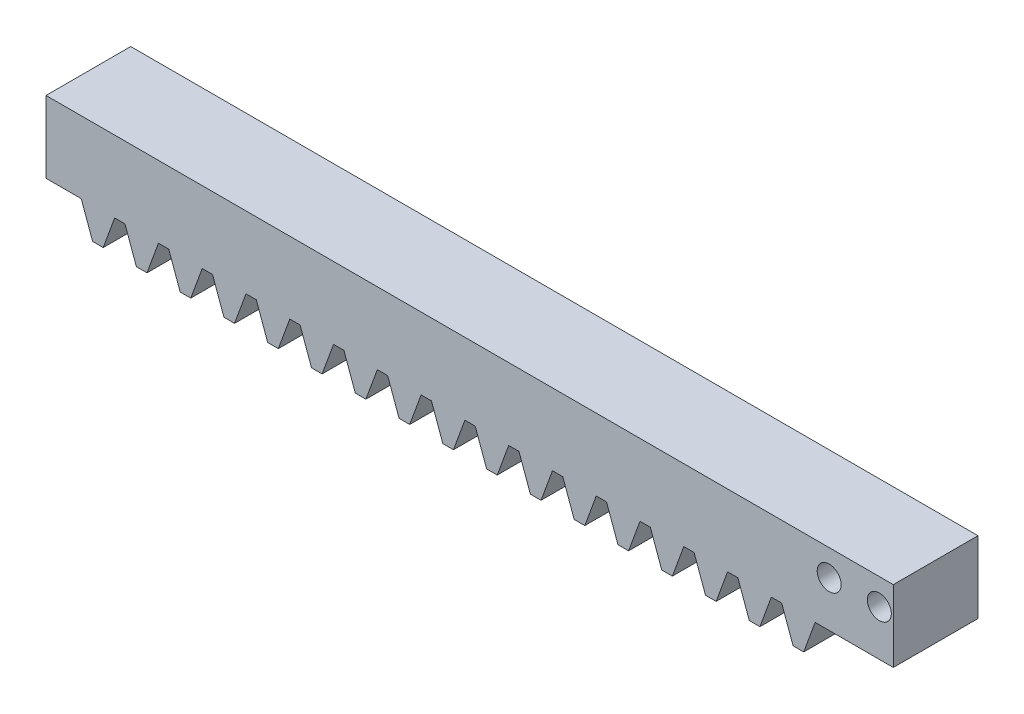
SolidWorks part; units mm, degrees
ref_plane "Front Plane" through (0, 0, 0) normal (0, 0, 1) x (1, 0, 0)
ref_plane "Top Plane" through (0, 0, 0) normal (0, 1, 0) x (1, 0, 0)
ref_plane "Right Plane" through (0, 0, 0) normal (1, 0, 0) x (0, 0, -1)
sketch "Sketch1" plane through (0, 0, 0) normal (0, 0, 1) x (1, 0, 0)
  line L0 (-80, 43.5) -> (-80, 30.625)
  line L1 (-80, 30.625) -> (-73.6867, 30.625)
  line L2 (-73.6867, 30.625) -> (-71.6394, 25)
  line L3 (-71.6394, 25) -> (-69.7323, 25)
  line L4 (-69.7323, 25) -> (-67.6849, 30.625)
  line L5 (-67.6849, 30.625) -> (-65.8328, 30.625)
  line L6 (-65.8328, 30.625) -> (-63.7854, 25)
  line L7 (-63.7854, 25) -> (-61.8783, 25)
  line L8 (-61.8783, 25) -> (-59.831, 30.625)
  line L9 (-59.831, 30.625) -> (-57.9788, 30.625)
  line L10 (-57.9788, 30.625) -> (-55.9314, 25)
  line L11 (-55.9314, 25) -> (-54.0243, 25)
  line L12 (-54.0243, 25) -> (-51.977, 30.625)
  line L13 (-51.977, 30.625) -> (-50.1248, 30.625)
  line L14 (-50.1248, 30.625) -> (-48.0775, 25)
  line L15 (-48.0775, 25) -> (-46.1703, 25)
  line L16 (-46.1703, 25) -> (-44.123, 30.625)
  line L17 (-44.123, 30.625) -> (-42.2708, 30.625)
  line L18 (-42.2708, 30.625) -> (-40.2235, 25)
  line L19 (-40.2235, 25) -> (-38.3163, 25)
  line L20 (-38.3163, 25) -> (-36.269, 30.625)
  line L21 (-36.269, 30.625) -> (-34.4168, 30.625)
  line L22 (-34.4168, 30.625) -> (-32.3695, 25)
  line L23 (-32.3695, 25) -> (-30.4624, 25)
  line L24 (-30.4624, 25) -> (-28.415, 30.625)
  line L25 (-28.415, 30.625) -> (-26.5628, 30.625)
  line L26 (-26.5628, 30.625) -> (-24.5155, 25)
  line L27 (-24.5155, 25) -> (-22.6084, 25)
  line L28 (-22.6084, 25) -> (-20.561, 30.625)
  line L29 (-20.561, 30.625) -> (-18.7089, 30.625)
  line L30 (-18.7089, 30.625) -> (-16.6615, 25)
  line L31 (-16.6615, 25) -> (-14.7544, 25)
  line L32 (-14.7544, 25) -> (-12.7071, 30.625)
  line L33 (-12.7071, 30.625) -> (-10.8549, 30.625)
  line L34 (-10.8549, 30.625) -> (-8.8076, 25)
  line L35 (-8.8076, 25) -> (-6.9004, 25)
  line L36 (-6.9004, 25) -> (-4.8531, 30.625)
  line L37 (-4.8531, 30.625) -> (-3.0009, 30.625)
  line L38 (-3.0009, 30.625) -> (-0.9536, 25)
  line L39 (-0.9536, 25) -> (0.9536, 25)
  line L40 (0.9536, 25) -> (3.0009, 30.625)
  line L41 (3.0009, 30.625) -> (4.8531, 30.625)
  line L42 (4.8531, 30.625) -> (6.9004, 25)
  line L43 (6.9004, 25) -> (8.8076, 25)
  line L44 (8.8076, 25) -> (10.8549, 30.625)
  line L45 (10.8549, 30.625) -> (12.7071, 30.625)
  line L46 (12.7071, 30.625) -> (14.7544, 25)
  line L47 (14.7544, 25) -> (16.6615, 25)
  line L48 (16.6615, 25) -> (18.7089, 30.625)
  line L49 (18.7089, 30.625) -> (20.561, 30.625)
  line L50 (20.561, 30.625) -> (22.6084, 25)
  line L51 (22.6084, 25) -> (24.5155, 25)
  line L52 (24.5155, 25) -> (26.5628, 30.625)
  line L53 (26.5628, 30.625) -> (28.415, 30.625)
  line L54 (28.415, 30.625) -> (30.4624, 25)
  line L55 (30.4624, 25) -> (32.3695, 25)
  line L56 (32.3695, 25) -> (34.4168, 30.625)
  line L57 (34.4168, 30.625) -> (36.269, 30.625)
  line L58 (36.269, 30.625) -> (38.3163, 25)
  line L59 (38.3163, 25) -> (40.2235, 25)
  line L60 (40.2235, 25) -> (42.2708, 30.625)
  line L61 (42.2708, 30.625) -> (44.123, 30.625)
  line L62 (44.123, 30.625) -> (46.1703, 25)
  line L63 (46.1703, 25) -> (48.0775, 25)
  line L64 (48.0775, 25) -> (50.1248, 30.625)
  line L65 (50.1248, 30.625) -> (51.977, 30.625)
  line L66 (51.977, 30.625) -> (54.0243, 25)
  line L67 (54.0243, 25) -> (55.9314, 25)
  line L68 (55.9314, 25) -> (57.9788, 30.625)
  line L69 (57.9788, 30.625) -> (72, 30.625)
  line L70 (72, 30.625) -> (72, 43.5)
  line L71 (72, 43.5) -> (-80, 43.5)
extrude "17 rack teeth - module 2.5 and 20 degrees" add sketch "Sketch1" along normal blind 15.2 from offset 42.4
sketch "Sketch2" plane through (0, 0, 0) normal (0, 0, 1) x (1, 0, 0)
  circle A0 centre (60.5, 38.8) radius 2.15
  circle A1 centre (69.5, 38.8) radius 2.15
extrude "Two crosshead joint through holes" cut sketch "Sketch2" along normal blind 15.2 from offset 42.4
